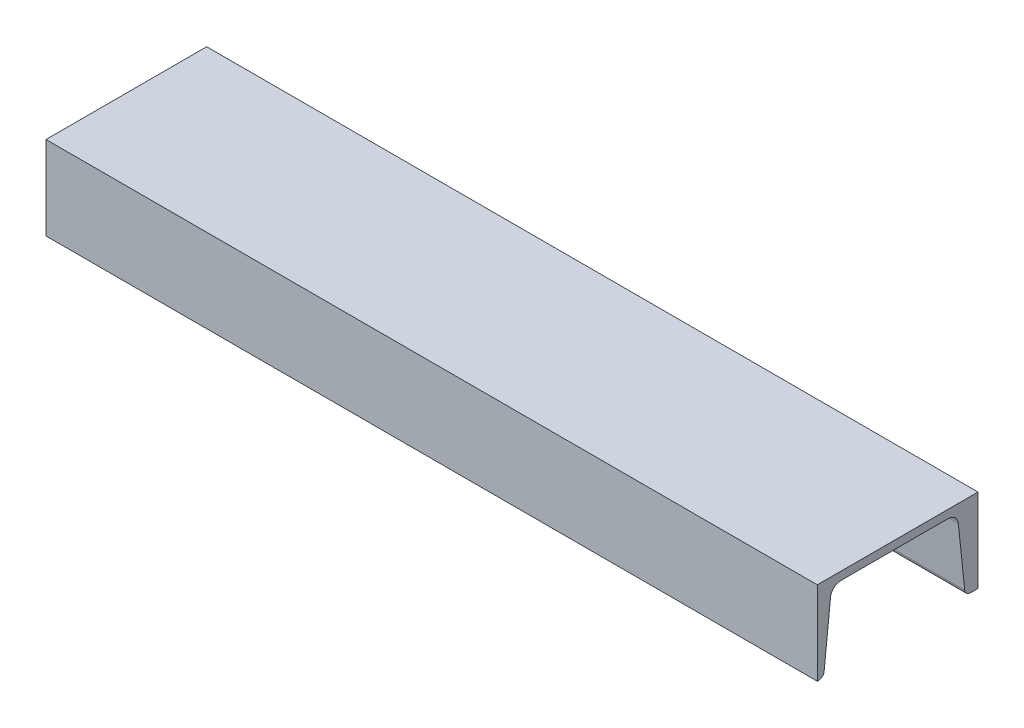
SolidWorks part; units mm, degrees
ref_plane "Front Plane" through (0, 0, 0) normal (0, 0, 1) x (1, 0, 0)
ref_plane "Top Plane" through (0, 0, 0) normal (0, 1, 0) x (1, 0, 0)
ref_plane "Right Plane" through (0, 0, 0) normal (1, 0, 0) x (0, 0, -1)
sketch "Sketch1" plane through (0, 0, 0) normal (0, 0, 1) x (1, 0, 0)
  line L0 (0, 0) -> (-600, 0)
other "C channel 120 X 12(1)"
ref_plane "Plane1" through (0, 0, 0) normal (-1, 0, 0) x (0, -1, 0)
sketch "Sketch11" plane through (0, 0, 0) normal (-1, 0, 0) x (0, -1, 0)
  line L0 (65, 125) -> (0, 125)
  line L1 (65, 0) -> (0, 0)
  line L2 (0, 125) -> (0, 0)
  line L6 (65, 125) -> (65, 124.1647)
  line L7 (65, 0) -> (65, 5.8453)
  line L12 (6.3, 106.74) -> (6.3, 23.27)
  line L17 (13.4638, 114.6962) -> (60.9704, 119.6893)
  line L18 (13.4638, 15.3138) -> (60.9704, 10.3207)
  arc A0 (60.9704, 119.6893) -> (65, 124.1647) centre (60.5, 124.1647) ccw
  arc A1 (60.9704, 10.3207) -> (65, 5.8453) centre (60.5, 5.8453) cw
  arc A9 (6.3, 23.27) -> (13.4638, 15.3138) centre (14.3, 23.27) ccw
  arc A10 (6.3, 106.74) -> (13.4638, 114.6962) centre (14.3, 106.74) cw
  point P8 (0, 62.5)
  point P9 (6.3, 65.005)
  point P10 (32.5, 125)
  point P11 (32.5, 0)
  point P12 (65, 9.8971)
  point P13 (65, 120.1129)
  point P14 (0, 0)
  dimension "D4" = 4.5
  dimension "RI" = 8
  dimension "D2" = 6
  dimension "D3" = 18.26
  dimension "Depth" = 125
  dimension "BF" = 65
  dimension "TW" = 6.3
  dimension "d1" = 83.47
